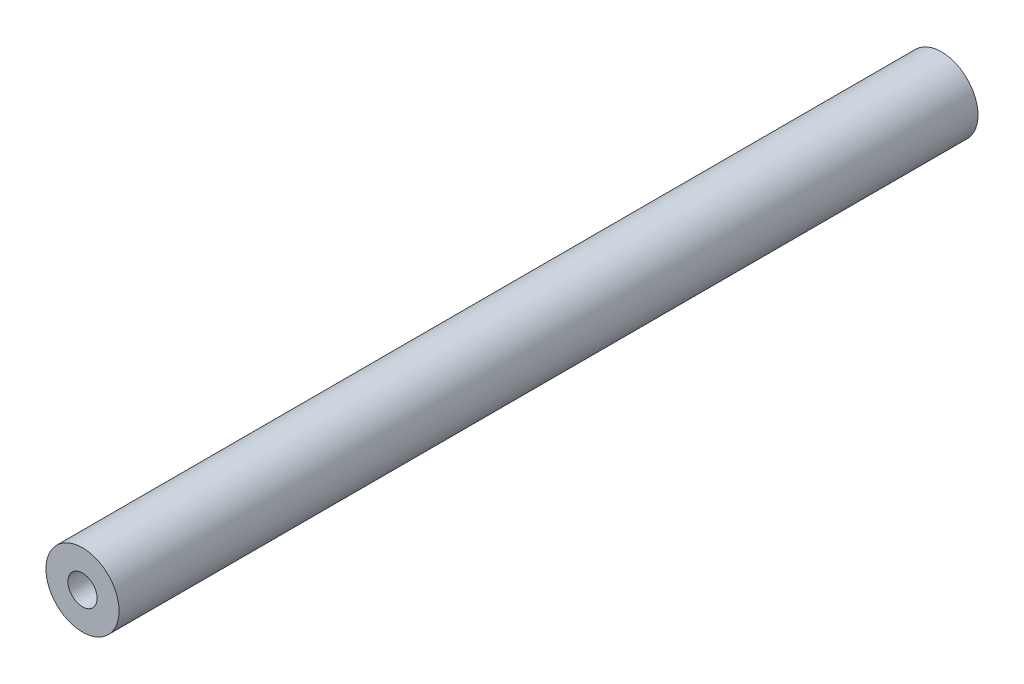
SolidWorks part; units mm, degrees
ref_plane "前视基准面" through (0, 0, 0) normal (0, 0, 1) x (1, 0, 0)
ref_plane "上视基准面" through (0, 0, 0) normal (0, 1, 0) x (1, 0, 0)
ref_plane "右视基准面" through (0, 0, 0) normal (1, 0, 0) x (0, 0, -1)
other "Configuration Table"
sketch "草图1" plane through (0, 0, 0) normal (0, 0, 1) x (1, 0, 0)
  circle A0 centre (0, 0) radius 4
  circle A1 centre (0, 0) radius 1.6
extrude "凸台-拉伸1" add sketch "草图1" along normal mid plane 94
